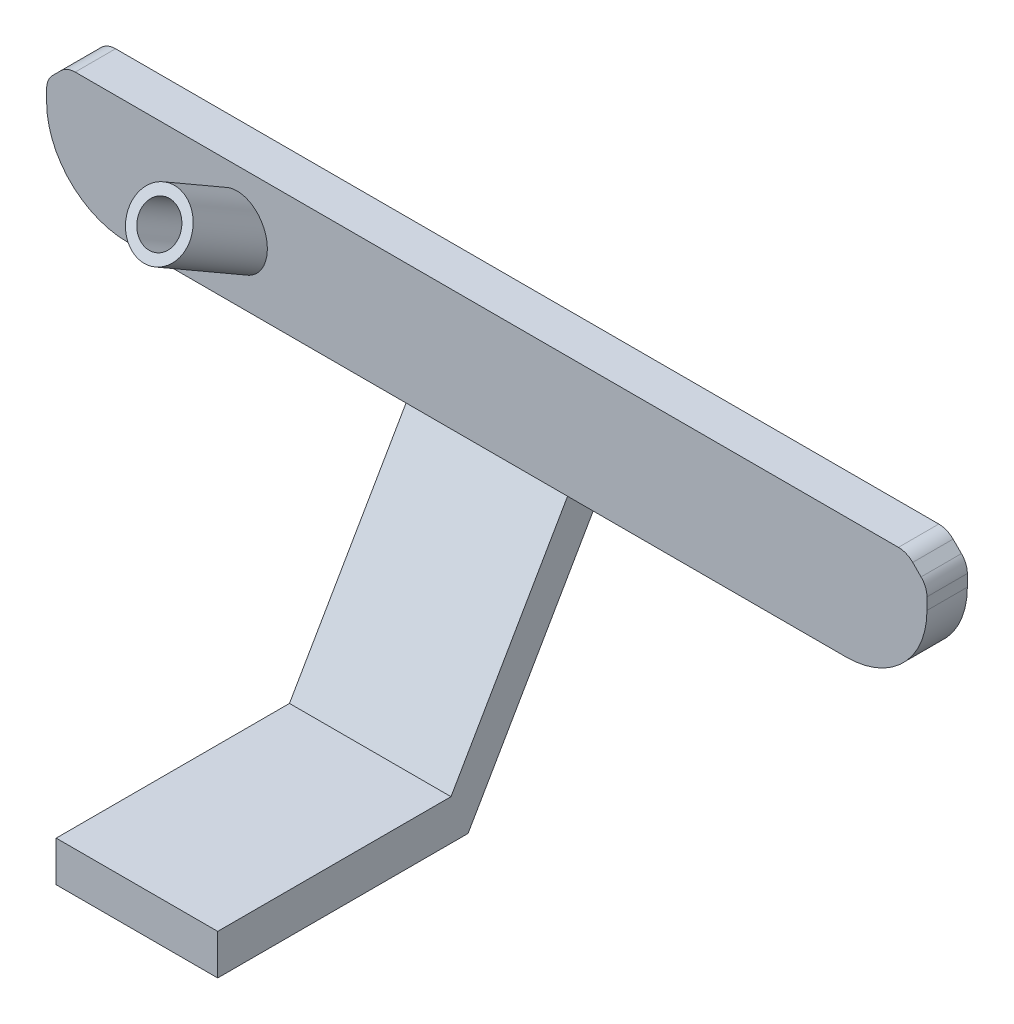
SolidWorks part; units mm, degrees
ref_plane "Front Plane" through (0, 0, 0) normal (0, 0, 1) x (1, 0, 0)
ref_plane "Top Plane" through (0, 0, 0) normal (0, 1, 0) x (1, 0, 0)
ref_plane "Right Plane" through (0, 0, 0) normal (1, 0, 0) x (0, 0, -1)
sketch "Sketch1" plane through (0, 0, 0) normal (0, 0, 1) x (1, 0, 0)
  line L1 (109, -15) -> (-109, -15)
  line L2 (109, -15) -> (109, 15)
  line L3 (109, 15) -> (-109, 15)
  line L4 (-109, -15) -> (-109, 15)
  line L5 (109, -15) -> (-109, 15) construction
  line L6 (109, 15) -> (-109, -15) construction
  point P0 (0, 0)
  dimension "D1" = 218
  dimension "D2" = 30
extrude "Boss-Extrude1" add sketch "Sketch1" along normal mid plane 10
fillet "Fillet1" radius 20 2 edges at (109, -15, 0) (-109, -15, 0)
ref_plane "Plane1" through (-61.85, 0, 0) normal (1, 0, 0) x (0, 0, -1)
sketch "Sketch3" plane through (-61.85, 0, 0) normal (1, 0, 0) x (0, 0, -1)
  line L0 (-20.4987, 18.4952) -> (-24.2487, 12)
  line L1 (-20.4987, 18.4952) -> (14.1423, -1.5048)
  line L2 (-24.2487, 12) -> (10.3923, -8)
  line L3 (14.1423, -1.5048) -> (10.3923, -8)
  line L4 (5, -15) -> (-5, -15) construction
  line L5 (-5, 5) -> (-5, -15) construction
  point P0 (0, -2)
  dimension "D1" = 40
  dimension "D2" = 28
  dimension "D3" = 7.5
  dimension "D4" = 13
  dimension "D5" = 120
revolve "Revolve1" add sketch "Sketch3" angle 360 about L2
sketch "Sketch4" plane through (0, 13.5, 23.3827) normal (0, 0.5, 0.866) x (1, 0, 0)
  circle A0 centre (-61.85, -1.7321) radius 5
  dimension "D1" = 10
extrude "Cut-Extrude2" cut sketch "Sketch4" against normal through all
sketch "Sketch5" plane through (0, 0, 0) normal (1, 0, 0) x (0, 0, -1)
  line L0 (5, -15) -> (-5, -15) construction
  line L1 (5, -15) -> (-5, -15)
  line L2 (5, -15) -> (-29.641, -75)
  line L3 (-29.641, -75) -> (-91.641, -75)
  line L4 (-5, -15) -> (-33.8675, -65)
  line L5 (-33.8675, -65) -> (-91.641, -65)
  line L6 (-91.641, -65) -> (-91.641, -75)
  dimension "D1" = 90
  dimension "D2" = 120
  dimension "D3" = 62
  dimension "D4" = 10
extrude "Boss-Extrude2" add sketch "Sketch5" along normal mid plane 40
chamfer "Chamfer2" distance 5 angle 45 2 edges at (-109, 15, 0) (109, 15, 0)
fillet "Fillet3" radius 5 4 edges at (104, 15, 0) (109, 10, 0) (-109, 10, 0) (-104, 15, 0)
